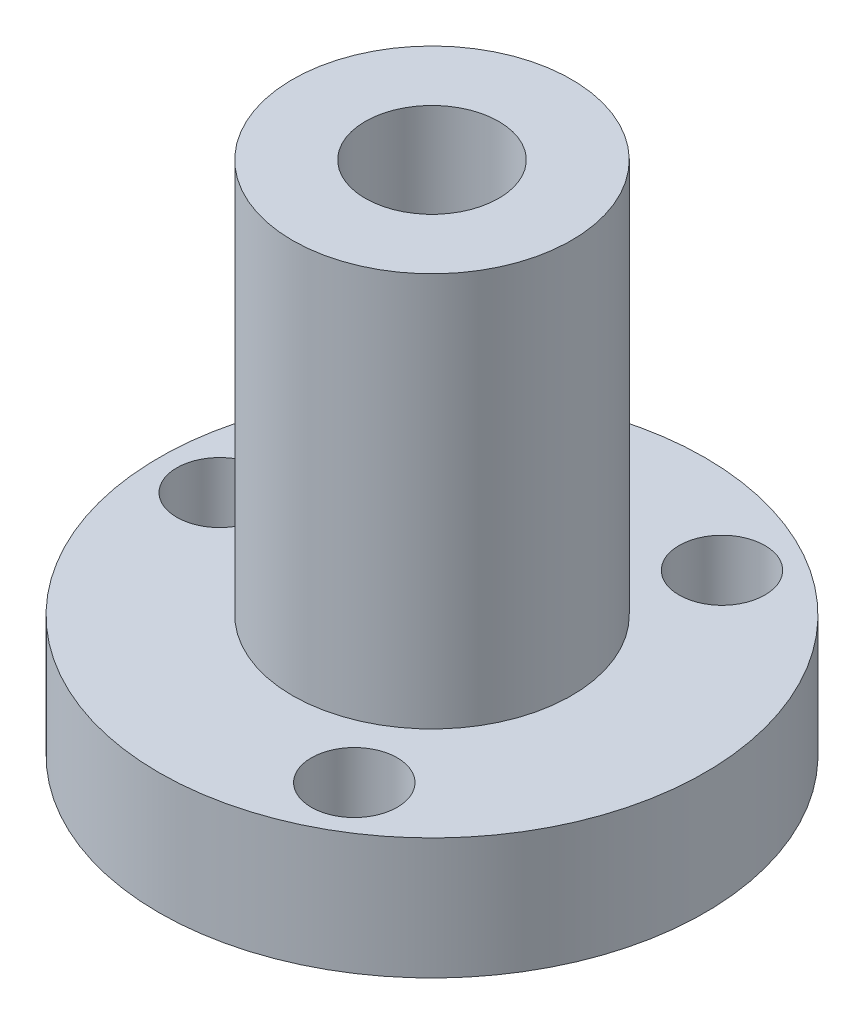
SolidWorks part; units mm, degrees
ref_plane "Front Plane" through (0, 0, 0) normal (0, 0, 1) x (1, 0, 0)
ref_plane "Top Plane" through (0, 0, 0) normal (0, 1, 0) x (1, 0, 0)
ref_plane "Right Plane" through (0, 0, 0) normal (1, 0, 0) x (0, 0, -1)
sketch "Sketch1" plane through (0, 0, 0) normal (0, 1, 0) x (1, 0, 0)
  circle A0 centre (0, 0) radius 14.2875
  dimension "D1" = 28.575
extrude "Boss-Extrude1" add sketch "Sketch1" along normal blind 6.35
sketch "Sketch2" plane through (0, 6.35, 0) normal (0, 1, 0) x (1, 0, 0)
  circle A0 centre (0, 0) radius 7.3025
  dimension "D1" = 14.605
extrude "Boss-Extrude2" add sketch "Sketch2" along normal blind 20.6375
sketch "Sketch3" plane through (0, 0, 0) normal (0, -1, 0) x (1, 0, 0)
  circle A0 centre (0, 0) radius 3.4925
  dimension "D1" = 6.985
extrude "Cut-Extrude1" cut sketch "Sketch3" against normal up to next
hole_wizard "#8 Clearance Hole1" positions "Sketch5" profile "Sketch4" hole size "#8" standard "ANSI Inch" end condition through all
sketch "Sketch5" plane through (0, 0, 0) normal (0, -1, 0) x (-1, 0, 0)
  line L0 (0, 0) -> (14.2875, 0) construction
  circle A0 centre (0, 0) radius 14.2875 construction
  point P10 (11.1125, 0)
  point P44 (-5.5562, -9.6237)
  point P45 (-5.5563, 9.6237)
  dimension "D1" = 11.1125
  dimension "D3" = 11.1125
  dimension "D4" = 11.1125
  dimension "D2" = 3
sketch "Sketch4" plane through (5.5563, 0, -9.6237) normal (1, 0, 0) x (0, 0, -1)
  line L0 (0, 0) -> (0, 26.9875)
  line L1 (0, 26.9875) -> (2.2479, 26.9875)
  line L2 (2.2479, 26.9875) -> (2.2479, 0)
  line L5 (2.2479, 0) -> (0, 0)
  line L11 (0, -6.35) -> (0, 107.95) construction
  dimension "Thru Hole Dia." = 4.4958
  dimension "Thru Hole Depth" = 26.9875
